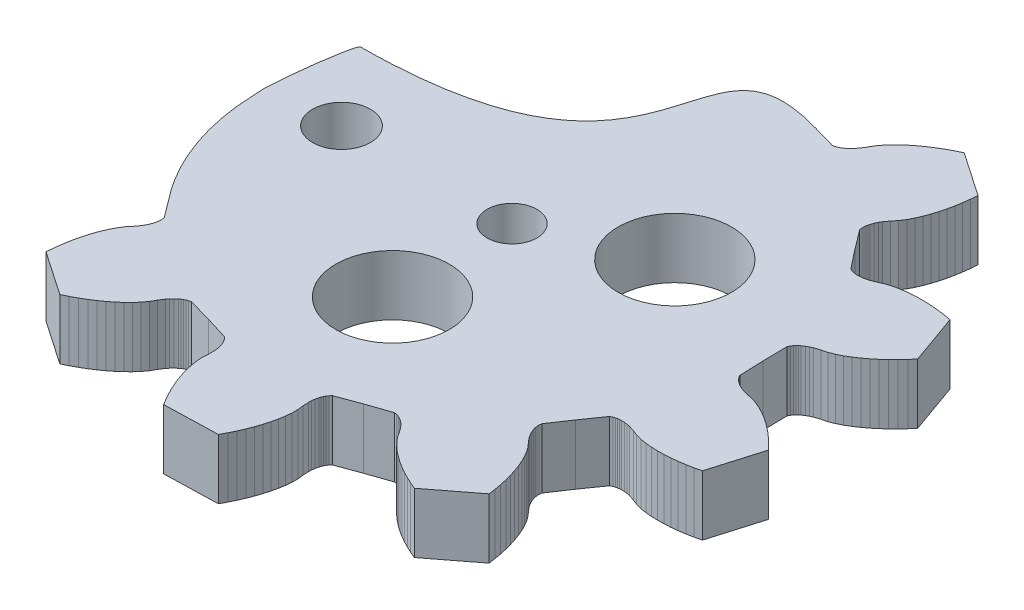
SolidWorks part; units mm, degrees
ref_plane "Front Plane" through (0, 0, 0) normal (0, 0, 1) x (1, 0, 0)
ref_plane "Top Plane" through (0, 0, 0) normal (0, 1, 0) x (1, 0, 0)
ref_plane "Right Plane" through (0, 0, 0) normal (1, 0, 0) x (0, 0, -1)
sketch "Sketch1" plane through (0, 0, 0) normal (0, 1, 0) x (1, 0, 0)
  line L0 (122.4346, 50.822) -> (125.4939, 50.8829) construction
  line L1 (123.9338, 52.3821) -> (123.9948, 49.3228) construction
  line L2 (133.0401, 47.3715) -> (133.2422, 41.3751) construction
  line L3 (136.1393, 44.4744) -> (130.143, 44.2722) construction
  line L4 (140.1684, 50.8222) -> (137.6333, 56.2585) construction
  line L5 (136.1826, 52.2729) -> (141.6191, 54.8079) construction
  line L109 (145.8722, 51.241) -> (145.8498, 52.524)
  line L110 (145.8498, 52.524) -> (145.9109, 52.6451)
  line L111 (145.9109, 52.6451) -> (145.9754, 52.7363)
  line L112 (145.9754, 52.7363) -> (146.0419, 52.8114)
  line L113 (146.0419, 52.8114) -> (146.1097, 52.8757)
  line L114 (146.1097, 52.8757) -> (146.1784, 52.932)
  line L115 (146.1784, 52.932) -> (146.3183, 53.0272)
  line L116 (146.3183, 53.0272) -> (146.4607, 53.1048)
  line L117 (146.4607, 53.1048) -> (146.6051, 53.1689)
  line L118 (146.6051, 53.1689) -> (146.8991, 53.2658)
  line L119 (146.8991, 53.2658) -> (147.1964, 53.3421)
  line L120 (147.1964, 53.3421) -> (147.4869, 53.4568)
  line L121 (147.4869, 53.4568) -> (147.7721, 53.5996)
  line L122 (147.7721, 53.5996) -> (148.0524, 53.7652)
  line L123 (148.0524, 53.7652) -> (148.328, 53.9506)
  line L124 (148.328, 53.9506) -> (148.5987, 54.1541)
  line L125 (148.5987, 54.1541) -> (148.8644, 54.3744)
  line L126 (148.8644, 54.3744) -> (149.1248, 54.611)
  line L127 (149.1248, 54.611) -> (149.3796, 54.8627)
  line L128 (149.3796, 54.8627) -> (149.6287, 55.1294)
  line L129 (149.6287, 55.1294) -> (149.8715, 55.4104)
  line L130 (149.8715, 55.4104) -> (148.9277, 58.0632)
  line L131 (148.9277, 58.0632) -> (148.562, 58.1275)
  line L132 (148.562, 58.1275) -> (148.2004, 58.1769)
  line L133 (148.2004, 58.1769) -> (147.8438, 58.2112)
  line L134 (147.8438, 58.2112) -> (147.4925, 58.23)
  line L135 (147.4925, 58.23) -> (147.1473, 58.2329)
  line L136 (147.1473, 58.2329) -> (146.809, 58.2196)
  line L137 (146.809, 58.2196) -> (146.4782, 58.1892)
  line L138 (146.4782, 58.1892) -> (146.1563, 58.1406)
  line L139 (146.1563, 58.1406) -> (145.8449, 58.0713)
  line L140 (145.8449, 58.0713) -> (145.5474, 57.9768)
  line L141 (145.5474, 57.9768) -> (145.2686, 57.848)
  line L142 (145.2686, 57.848) -> (144.9795, 57.7375)
  line L143 (144.9795, 57.7375) -> (144.827, 57.6959)
  line L144 (144.827, 57.6959) -> (144.6676, 57.6661)
  line L145 (144.6676, 57.6661) -> (144.4991, 57.6516)
  line L146 (144.4991, 57.6516) -> (144.4102, 57.6519)
  line L147 (144.4102, 57.6519) -> (144.3171, 57.6589)
  line L148 (144.3171, 57.6589) -> (144.2182, 57.6752)
  line L149 (144.2182, 57.6752) -> (144.1105, 57.705)
  line L150 (144.1105, 57.705) -> (143.9866, 57.7603)
  line L151 (143.9866, 57.7603) -> (143.1935, 58.7691)
  line L152 (143.1935, 58.7691) -> (142.4211, 59.794)
  line L153 (142.4211, 59.794) -> (142.3995, 59.9281)
  line L154 (142.3995, 59.9281) -> (142.3981, 60.0397)
  line L155 (142.3981, 60.0397) -> (142.4078, 60.1395)
  line L156 (142.4078, 60.1395) -> (142.4247, 60.2312)
  line L157 (142.4247, 60.2312) -> (142.4473, 60.3173)
  line L158 (142.4473, 60.3173) -> (142.5044, 60.4765)
  line L159 (142.5044, 60.4765) -> (142.5741, 60.623)
  line L160 (142.5741, 60.623) -> (142.6532, 60.7597)
  line L161 (142.6532, 60.7597) -> (142.8342, 61.0109)
  line L162 (142.8342, 61.0109) -> (143.0298, 61.2474)
  line L163 (143.0298, 61.2474) -> (143.1975, 61.511)
  line L164 (143.1975, 61.511) -> (143.3441, 61.7942)
  line L165 (143.3441, 61.7942) -> (143.4735, 62.0929)
  line L166 (143.4735, 62.0929) -> (143.5874, 62.4049)
  line L167 (143.5874, 62.4049) -> (143.6869, 62.7286)
  line L168 (143.6869, 62.7286) -> (143.7724, 63.0631)
  line L169 (143.7724, 63.0631) -> (143.8441, 63.4075)
  line L170 (143.8441, 63.4075) -> (143.9022, 63.7609)
  line L171 (143.9022, 63.7609) -> (143.947, 64.1231)
  line L172 (143.947, 64.1231) -> (143.9783, 64.4931)
  line L173 (143.9783, 64.4931) -> (141.6555, 66.0844)
  line L174 (141.6555, 66.0844) -> (141.3217, 65.9216)
  line L175 (141.3217, 65.9216) -> (141.0002, 65.749)
  line L176 (141.0002, 65.749) -> (140.6916, 65.5671)
  line L177 (140.6916, 65.5671) -> (140.3964, 65.3758)
  line L178 (140.3964, 65.3758) -> (140.1153, 65.1754)
  line L179 (140.1153, 65.1754) -> (139.8493, 64.9658)
  line L180 (139.8493, 64.9658) -> (139.5996, 64.7468)
  line L181 (139.5996, 64.7468) -> (139.3679, 64.5182)
  line L182 (139.3679, 64.5182) -> (139.1567, 64.279)
  line L183 (139.1567, 64.279) -> (138.9714, 64.0276)
  line L184 (138.9714, 64.0276) -> (138.8216, 63.7597)
  line L185 (138.8216, 63.7597) -> (138.6528, 63.5003)
  line L186 (138.6528, 63.5003) -> (138.5538, 63.3771)
  line L187 (138.5538, 63.3771) -> (138.4424, 63.2593)
  line L188 (138.4424, 63.2593) -> (138.3144, 63.1485)
  line L189 (138.3144, 63.1485) -> (138.2424, 63.0964)
  line L190 (138.2424, 63.0964) -> (138.163, 63.0474)
  line L191 (138.163, 63.0474) -> (138.0734, 63.0023)
  line L192 (138.0734, 63.0023) -> (137.9689, 62.9632)
  line L193 (137.9689, 62.9632) -> (137.8361, 62.9351)
  line L194 (137.8361, 62.9351) -> (136.6014, 63.2852)
  line L195 (120.2031, 50.5244) -> (120.2391, 49.8531)
  line L196 (122.7026, 42.9968) -> (123.475, 41.9719)
  line L197 (123.475, 41.9719) -> (123.4967, 41.8379)
  line L198 (123.4967, 41.8379) -> (123.498, 41.7262)
  line L199 (123.498, 41.7262) -> (123.4885, 41.6265)
  line L200 (123.4885, 41.6265) -> (123.4713, 41.5347)
  line L201 (123.4713, 41.5347) -> (123.4488, 41.4486)
  line L202 (123.4488, 41.4486) -> (123.3917, 41.2895)
  line L203 (123.3917, 41.2895) -> (123.322, 41.1429)
  line L204 (123.322, 41.1429) -> (123.2429, 41.0061)
  line L205 (123.2429, 41.0061) -> (123.0621, 40.755)
  line L206 (123.0621, 40.755) -> (122.8664, 40.5185)
  line L207 (122.8664, 40.5185) -> (122.6987, 40.255)
  line L208 (122.6987, 40.255) -> (122.5521, 39.9717)
  line L209 (122.5521, 39.9717) -> (122.4226, 39.673)
  line L210 (122.4226, 39.673) -> (122.3086, 39.3611)
  line L211 (122.3086, 39.3611) -> (122.2092, 39.0373)
  line L212 (122.2092, 39.0373) -> (122.1238, 38.7029)
  line L213 (122.1238, 38.7029) -> (122.0521, 38.3585)
  line L214 (122.0521, 38.3585) -> (121.9939, 38.0049)
  line L215 (121.9939, 38.0049) -> (121.9492, 37.6429)
  line L216 (121.9492, 37.6429) -> (121.9178, 37.2728)
  line L217 (121.9178, 37.2728) -> (124.2407, 35.6815)
  line L218 (124.2407, 35.6815) -> (124.5745, 35.8444)
  line L219 (124.5745, 35.8444) -> (124.896, 36.017)
  line L220 (124.896, 36.017) -> (125.2046, 36.1989)
  line L221 (125.2046, 36.1989) -> (125.4998, 36.39)
  line L222 (125.4998, 36.39) -> (125.7809, 36.5905)
  line L223 (125.7809, 36.5905) -> (126.0468, 36.8001)
  line L224 (126.0468, 36.8001) -> (126.2965, 37.0191)
  line L225 (126.2965, 37.0191) -> (126.5282, 37.2478)
  line L226 (126.5282, 37.2478) -> (126.7395, 37.4867)
  line L227 (126.7395, 37.4867) -> (126.9246, 37.7384)
  line L228 (126.9246, 37.7384) -> (127.0746, 38.0063)
  line L229 (127.0746, 38.0063) -> (127.2434, 38.2656)
  line L230 (127.2434, 38.2656) -> (127.3423, 38.3889)
  line L231 (127.3423, 38.3889) -> (127.4538, 38.5066)
  line L232 (127.4538, 38.5066) -> (127.5816, 38.6175)
  line L233 (127.5816, 38.6175) -> (127.6537, 38.6695)
  line L234 (127.6537, 38.6695) -> (127.7332, 38.7186)
  line L235 (127.7332, 38.7186) -> (127.8227, 38.7636)
  line L236 (127.8227, 38.7636) -> (127.9273, 38.8026)
  line L237 (127.9273, 38.8026) -> (128.06, 38.8309)
  line L238 (128.06, 38.8309) -> (129.2947, 38.4808)
  line L239 (129.2947, 38.4808) -> (130.5221, 38.1055)
  line L240 (130.5221, 38.1055) -> (130.6183, 38.01)
  line L241 (130.6183, 38.01) -> (130.6851, 37.9204)
  line L242 (130.6851, 37.9204) -> (130.7359, 37.834)
  line L243 (130.7359, 37.834) -> (130.7761, 37.7498)
  line L244 (130.7761, 37.7498) -> (130.8085, 37.6669)
  line L245 (130.8085, 37.6669) -> (130.8557, 37.5046)
  line L246 (130.8557, 37.5046) -> (130.8855, 37.345)
  line L247 (130.8855, 37.345) -> (130.9018, 37.1879)
  line L248 (130.9018, 37.1879) -> (130.9031, 36.8785)
  line L249 (130.9031, 36.8785) -> (130.8839, 36.5721)
  line L250 (130.8839, 36.5721) -> (130.903, 36.2604)
  line L251 (130.903, 36.2604) -> (130.951, 35.9449)
  line L252 (130.951, 35.9449) -> (131.0218, 35.6272)
  line L253 (131.0218, 35.6272) -> (131.1129, 35.3079)
  line L254 (131.1129, 35.3079) -> (131.2228, 34.9875)
  line L255 (131.2228, 34.9875) -> (131.3503, 34.6667)
  line L256 (131.3503, 34.6667) -> (131.4947, 34.3459)
  line L257 (131.4947, 34.3459) -> (131.6554, 34.0257)
  line L258 (131.6554, 34.0257) -> (131.8321, 33.7065)
  line L259 (131.8321, 33.7065) -> (132.0242, 33.3886)
  line L260 (132.0242, 33.3886) -> (134.8388, 33.4666)
  line L261 (134.8388, 33.4666) -> (135.0131, 33.7946)
  line L262 (135.0131, 33.7946) -> (135.1717, 34.1231)
  line L263 (135.1717, 34.1231) -> (135.3145, 34.4518)
  line L264 (135.3145, 34.4518) -> (135.441, 34.78)
  line L265 (135.441, 34.78) -> (135.5506, 35.1073)
  line L266 (135.5506, 35.1073) -> (135.6425, 35.4333)
  line L267 (135.6425, 35.4333) -> (135.7157, 35.7572)
  line L268 (135.7157, 35.7572) -> (135.769, 36.0784)
  line L269 (135.769, 36.0784) -> (135.7993, 36.3959)
  line L270 (135.7993, 36.3959) -> (135.8013, 36.7083)
  line L271 (135.8013, 36.7083) -> (135.765, 37.0131)
  line L272 (135.765, 37.0131) -> (135.7493, 37.3222)
  line L273 (135.7493, 37.3222) -> (135.7568, 37.4801)
  line L274 (135.7568, 37.4801) -> (135.7778, 37.6408)
  line L275 (135.7778, 37.6408) -> (135.8159, 37.8057)
  line L276 (135.8159, 37.8057) -> (135.8437, 37.8901)
  line L277 (135.8437, 37.8901) -> (135.8792, 37.9765)
  line L278 (135.8792, 37.9765) -> (135.9251, 38.0656)
  line L279 (135.9251, 38.0656) -> (135.9868, 38.1586)
  line L280 (135.9868, 38.1586) -> (136.0777, 38.2595)
  line L281 (136.0777, 38.2595) -> (137.2823, 38.7019)
  line L282 (137.2823, 38.7019) -> (138.4956, 39.1198)
  line L283 (138.4956, 39.1198) -> (138.6297, 39.099)
  line L284 (138.6297, 39.099) -> (138.7364, 39.0659)
  line L285 (138.7364, 39.0659) -> (138.8283, 39.0259)
  line L286 (138.8283, 39.0259) -> (138.9103, 38.9813)
  line L287 (138.9103, 38.9813) -> (138.9852, 38.9334)
  line L288 (138.9852, 38.9334) -> (139.119, 38.8297)
  line L289 (139.119, 38.8297) -> (139.2367, 38.7182)
  line L290 (139.2367, 38.7182) -> (139.3423, 38.6006)
  line L291 (139.3423, 38.6006) -> (139.5253, 38.3512)
  line L292 (139.5253, 38.3512) -> (139.6897, 38.092)
  line L293 (139.6897, 38.092) -> (139.8886, 37.851)
  line L294 (139.8886, 37.851) -> (140.1127, 37.624)
  line L295 (140.1127, 37.624) -> (140.3568, 37.4086)
  line L296 (140.3568, 37.4086) -> (140.6182, 37.2038)
  line L297 (140.6182, 37.2038) -> (140.8954, 37.0092)
  line L298 (140.8954, 37.0092) -> (141.1872, 36.8246)
  line L299 (141.1872, 36.8246) -> (141.4925, 36.65)
  line L300 (141.4925, 36.65) -> (141.8107, 36.4854)
  line L301 (141.8107, 36.4854) -> (142.1412, 36.3309)
  line L302 (142.1412, 36.3309) -> (142.4835, 36.1867)
  line L303 (142.4835, 36.1867) -> (144.7147, 37.9042)
  line L304 (144.7147, 37.9042) -> (144.6629, 38.272)
  line L305 (144.6629, 38.272) -> (144.5982, 38.631)
  line L306 (144.5982, 38.631) -> (144.5206, 38.9808)
  line L307 (144.5206, 38.9808) -> (144.43, 39.3207)
  line L308 (144.43, 39.3207) -> (144.3261, 39.6499)
  line L309 (144.3261, 39.6499) -> (144.2089, 39.9677)
  line L310 (144.2089, 39.9677) -> (144.0779, 40.2729)
  line L311 (144.0779, 40.2729) -> (143.9321, 40.5638)
  line L312 (143.9321, 40.5638) -> (143.77, 40.8386)
  line L313 (143.77, 40.8386) -> (143.588, 41.0924)
  line L314 (143.588, 41.0924) -> (143.3795, 41.3177)
  line L315 (143.3795, 41.3177) -> (143.1849, 41.5586)
  line L316 (143.1849, 41.5586) -> (143.0984, 41.6906)
  line L317 (143.0984, 41.6906) -> (143.0208, 41.8331)
  line L318 (143.0208, 41.8331) -> (142.9549, 41.9889)
  line L319 (142.9549, 41.9889) -> (142.9276, 42.0735)
  line L320 (142.9276, 42.0735) -> (142.9056, 42.1642)
  line L321 (142.9056, 42.1642) -> (142.8905, 42.2633)
  line L322 (142.8905, 42.2633) -> (142.8856, 42.3748)
  line L323 (142.8856, 42.3748) -> (142.8998, 42.5098)
  line L324 (142.8998, 42.5098) -> (143.6143, 43.5759)
  line L325 (143.6143, 43.5759) -> (144.3503, 44.6272)
  line L326 (144.3503, 44.6272) -> (144.4711, 44.6892)
  line L327 (144.4711, 44.6892) -> (144.5768, 44.7249)
  line L328 (144.5768, 44.7249) -> (144.6748, 44.7466)
  line L329 (144.6748, 44.7466) -> (144.7673, 44.7588)
  line L330 (144.7673, 44.7588) -> (144.856, 44.764)
  line L331 (144.856, 44.764) -> (145.0251, 44.7588)
  line L332 (145.0251, 44.7588) -> (145.1859, 44.7379)
  line L333 (145.1859, 44.7379) -> (145.3405, 44.7048)
  line L334 (145.3405, 44.7048) -> (145.6352, 44.6105)
  line L335 (145.6352, 44.6105) -> (145.9207, 44.4975)
  line L336 (145.9207, 44.4975) -> (146.2231, 44.4193)
  line L337 (146.2231, 44.4193) -> (146.5379, 44.3676)
  line L338 (146.5379, 44.3676) -> (146.862, 44.3367)
  line L339 (146.862, 44.3367) -> (147.1937, 44.3247)
  line L340 (147.1937, 44.3247) -> (147.5324, 44.3301)
  line L341 (147.5324, 44.3301) -> (147.8769, 44.3522)
  line L342 (147.8769, 44.3522) -> (148.2266, 44.3906)
  line L343 (148.2266, 44.3906) -> (148.5809, 44.4444)
  line L344 (148.5809, 44.4444) -> (148.939, 44.5137)
  line L345 (148.939, 44.5137) -> (149.3006, 44.5982)
  line L346 (149.3006, 44.5982) -> (150.0962, 47.2993)
  line L347 (150.0962, 47.2993) -> (149.8382, 47.5662)
  line L348 (149.8382, 47.5662) -> (149.5747, 47.8187)
  line L349 (149.5747, 47.8187) -> (149.3064, 48.0562)
  line L350 (149.3064, 48.0562) -> (149.0332, 48.2778)
  line L351 (149.0332, 48.2778) -> (148.7557, 48.483)
  line L352 (148.7557, 48.483) -> (148.4741, 48.6712)
  line L353 (148.4741, 48.6712) -> (148.1887, 48.8411)
  line L354 (148.1887, 48.8411) -> (147.8998, 48.9909)
  line L355 (147.8998, 48.9909) -> (147.6071, 49.1179)
  line L356 (147.6071, 49.1179) -> (147.3106, 49.2163)
  line L357 (147.3106, 49.2163) -> (147.0096, 49.276)
  line L358 (147.0096, 49.276) -> (146.7108, 49.3565)
  line L359 (146.7108, 49.3565) -> (146.563, 49.4124)
  line L360 (146.563, 49.4124) -> (146.4164, 49.4821)
  line L361 (146.4164, 49.4821) -> (146.2716, 49.5694)
  line L362 (146.2716, 49.5694) -> (146.1997, 49.6219)
  line L363 (146.1997, 49.6219) -> (146.1286, 49.6823)
  line L364 (146.1286, 49.6823) -> (146.0581, 49.7535)
  line L365 (146.0581, 49.7535) -> (145.9886, 49.8411)
  line L366 (145.9886, 49.8411) -> (145.9208, 49.9585)
  line L367 (145.9208, 49.9585) -> (145.8722, 51.241)
  circle A0 centre (123.9642, 50.8525) radius 1.53
  circle A1 centre (132.9481, 50.883) radius 1.3158
  circle A2 centre (138.9008, 53.5404) radius 2.9992
  circle A3 centre (133.1411, 44.3733) radius 2.9999
  spline S192 degree 3 poles (136.6014, 63.2852) (128.1929, 65.715) (137.2502, 55.0352) (120.848, 54.9694) knots 0.326996 0.326996 0.326996 0.326996 0.330798 0.330798 0.330798 0.330798
  spline S193 degree 3 poles (120.848, 54.9694) (120.6706, 54.9506) (120.271, 52.255) (120.2031, 50.5244) knots 0.330798 0.330798 0.330798 0.330798 0.334601 0.334601 0.334601 0.334601
  spline S194 degree 3 poles (120.2391, 49.8531) (120.3825, 46.3033) (121.9458, 43.9607) (122.7026, 42.9968) knots 0.338403 0.338403 0.338403 0.338403 0.342205 0.342205 0.342205 0.342205
extrude "Boss-Extrude1" add sketch "Sketch1" along normal blind 3.175
